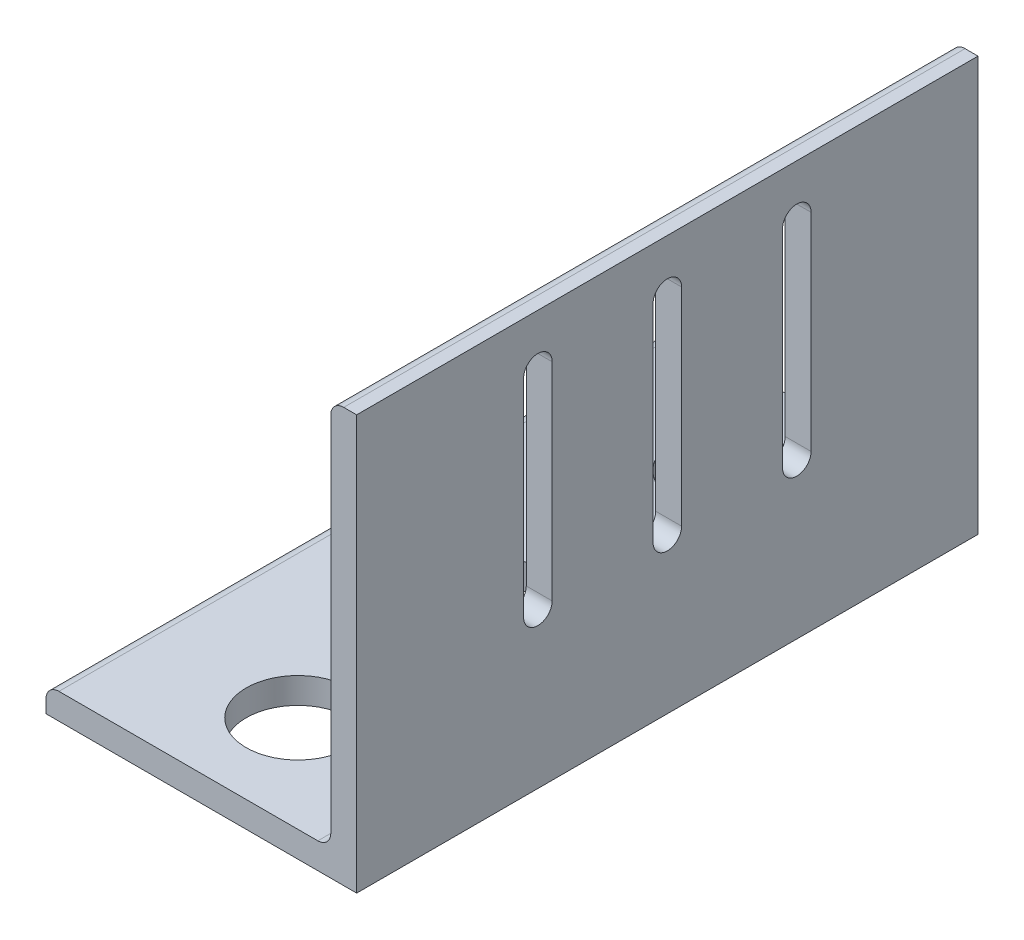
SolidWorks part; units mm, degrees
ref_plane "Front Plane" through (0, 0, 0) normal (0, 0, 1) x (1, 0, 0)
ref_plane "Top Plane" through (0, 0, 0) normal (0, 1, 0) x (1, 0, 0)
ref_plane "Right Plane" through (0, 0, 0) normal (1, 0, 0) x (0, 0, -1)
sketch "Sketch2" plane through (0, 0, 0) normal (0, 0, 1) x (1, 0, 0)
  line L0 (-38.1, 0) -> (38.1, 0)
  line L1 (38.1, 0) -> (38.1, 101.6)
  line L2 (38.1, 101.6) -> (31.75, 101.6) construction
  line L3 (31.75, 98.425) -> (31.75, 9.525)
  line L4 (28.575, 6.35) -> (-34.925, 6.35)
  line L5 (-38.1, 0) -> (-38.1, 6.35) construction
  line L6 (34.925, 101.6) -> (38.1, 101.6)
  line L7 (-38.1, 3.175) -> (-38.1, 0)
  arc A0 (31.75, 98.425) -> (34.925, 101.6) centre (34.925, 98.425) cw
  arc A1 (-38.1, 3.175) -> (-34.925, 6.35) centre (-34.925, 3.175) cw
  arc A2 (31.75, 9.525) -> (28.575, 6.35) centre (28.575, 9.525) cw
  dimension "Vert" = 101.6
  dimension "Horz" = 76.2
  dimension "Thickness" = 6.35
extrude "Boss-Extrude1" add sketch "Sketch2" along normal mid plane 152.4
ref_plane "Contact Plane 1" through (0, 6.35, 0) normal (0, 1, 0) x (1, 0, 0)
ref_plane "Contact Plane 2" through (31.75, 0, 0) normal (-1, 0, 0) x (0, 0, 1)
sketch "Sketch3" plane through (38.1, 0, 0) normal (1, 0, 0) x (0, 0, -1)
  line L0 (-31.75, 88.9) -> (-31.75, 38.1) construction
  line L1 (-28.25, 88.9) -> (-28.25, 38.1)
  line L2 (-35.25, 88.9) -> (-35.25, 38.1)
  line L3 (0, 0) -> (0, 101.6) construction
  line L4 (-76.2, 0) -> (76.2, 0) construction
  line L5 (-76.2, 101.6) -> (76.2, 101.6) construction
  line L6 (31.75, 88.9) -> (31.75, 38.1) construction
  line L7 (28.25, 88.9) -> (28.25, 38.1)
  line L8 (35.25, 88.9) -> (35.25, 38.1)
  line L9 (0, 88.9) -> (0, 38.1) construction
  line L10 (3.5, 88.9) -> (3.5, 38.1)
  line L11 (-3.5, 88.9) -> (-3.5, 38.1)
  arc A0 (-28.25, 88.9) -> (-35.25, 88.9) centre (-31.75, 88.9) ccw
  arc A1 (-35.25, 38.1) -> (-28.25, 38.1) centre (-31.75, 38.1) ccw
  arc A2 (28.25, 88.9) -> (35.25, 88.9) centre (31.75, 88.9) cw
  arc A3 (35.25, 38.1) -> (28.25, 38.1) centre (31.75, 38.1) cw
  arc A4 (3.5, 88.9) -> (-3.5, 88.9) centre (0, 88.9) ccw
  arc A5 (-3.5, 38.1) -> (3.5, 38.1) centre (0, 38.1) ccw
  point P2 (-31.75, 63.5)
  point P15 (31.75, 63.5)
  point P22 (0, 63.5)
  dimension "D1" = 3.5
  dimension "D3" = 31.75
  dimension "D5" = 3.5
  dimension "D2" = 50.8
  dimension "D4" = 63.5
  dimension "D6" = 50.8
  dimension "D7" = 63.5
extrude "Cut-Extrude1" cut sketch "Sketch3" against normal blind 10
sketch "Sketch4" plane through (0, 0, 0) normal (0, -1, 0) x (1, 0, 0)
  circle A2 centre (0, 0) radius 10
  circle A3 centre (0, 52.5) radius 12.7
  circle A4 centre (0, -52.5) radius 12.7
  dimension "D3" = 20
  dimension "D6" = 25.4
  dimension "D7" = 52.5
  dimension "D8" = 52.5
extrude "Cut-Extrude2" cut sketch "Sketch4" against normal blind 10
